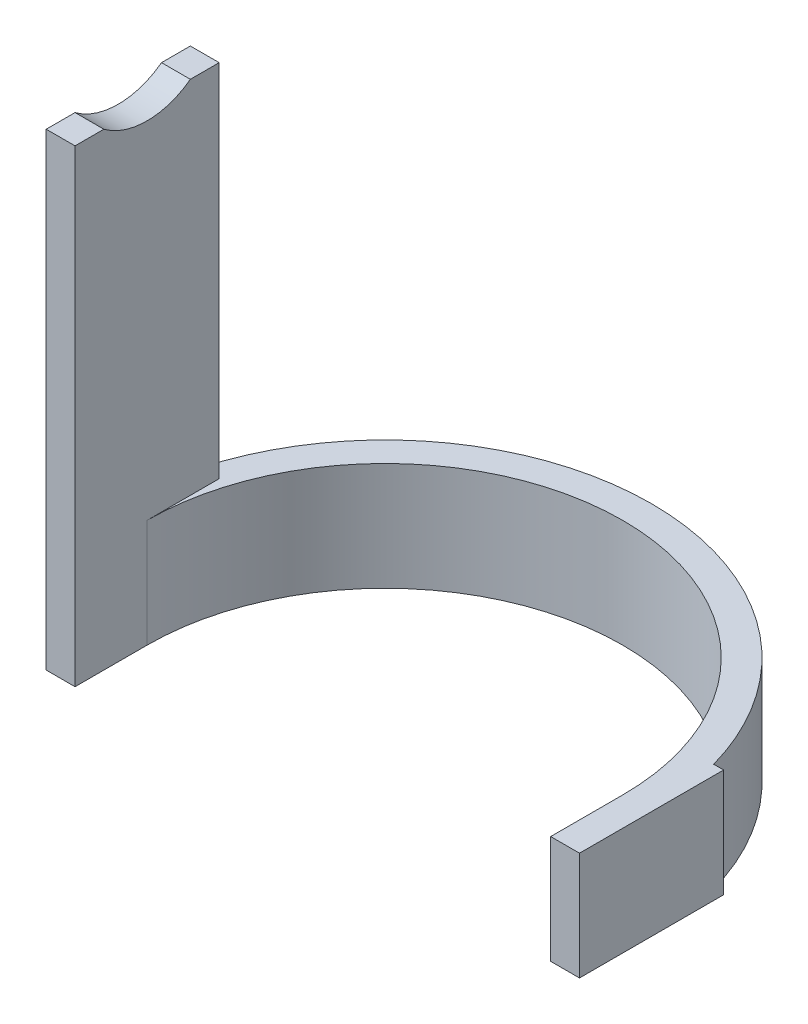
SolidWorks part; units mm, degrees
ref_plane "Front" through (0, 0, 0) normal (0, 0, 1) x (1, 0, 0)
ref_plane "Top" through (0, 0, 0) normal (0, 1, 0) x (1, 0, 0)
ref_plane "Right" through (0, 0, 0) normal (1, 0, 0) x (0, 0, -1)
sketch "草图1" plane through (0, 0, 0) normal (0, 1, 0) x (1, 0, 0)
  line L0 (-72.3418, 0) -> (74, 0) construction
  line L1 (0, 74) -> (0, -74) construction
  line L3 (-74, 20) -> (-71.2461, 20)
  line L4 (-74, 20) -> (-74, -20)
  line L5 (-74, -20) -> (-66, -20)
  line L6 (-66, 0) -> (-66, -20)
  line L7 (74, 20) -> (71.2461, 20)
  line L8 (74, 20) -> (74, -20)
  line L9 (74, -20) -> (66, -20)
  line L10 (66, 0) -> (66, -20)
  arc A0 (71.2461, 20) -> (-71.2461, 20) centre (0, 0) ccw
  arc A1 (66, 0) -> (-66, 0) centre (0, 0) ccw
  dimension "D1" = 40
  dimension "D2" = 20
  dimension "D3" = 8
  dimension "D4" = 8
  dimension "D6" = 40
  dimension "D7" = 20
extrude "凸台-拉伸1" add sketch "草图1" along normal blind 30
sketch "草图2" plane through (0, 30, 0) normal (0, 1, 0) x (1, 0, 0)
  line L1 (-74, -20) -> (-66, -20)
  line L2 (-74, -20) -> (-74, 20)
  line L3 (-74, 20) -> (-66, 20)
  line L4 (-66, -20) -> (-66, 20)
  line L5 (66, -20) -> (74, -20)
  line L6 (66, -20) -> (66, 20)
  line L7 (66, 20) -> (74, 20)
  line L8 (74, -20) -> (74, 20)
  dimension "D1" = 8
extrude "凸台-拉伸2" add sketch "草图2" along normal blind 100
sketch "草图3" plane through (-74, 0, 0) normal (-1, 0, 0) x (0, 0, 1)
  line L0 (-20, 130) -> (20, 130) construction
  circle A0 centre (0, 146) radius 20
  dimension "D1" = 16
extrude "切除-拉伸1" cut sketch "草图3" against normal through all
sketch "草图4" plane through (-74, 0, 0) normal (-1, 0, 0) x (0, 0, 1)
  line L1 (-20, 30) -> (29.7839, 30)
  line L2 (-20, 30) -> (-20, 136.1459)
  line L3 (-20, 136.1459) -> (29.7839, 136.1459)
  line L4 (29.7839, 30) -> (29.7839, 136.1459)
sketch "草图5" plane through (74, 0, 0) normal (1, 0, 0) x (0, 0, -1)
  line L1 (20, 30) -> (-67.0077, 30)
  line L2 (20, 30) -> (20, 135.1923)
  line L3 (20, 135.1923) -> (-67.0077, 135.1923)
  line L4 (-67.0077, 30) -> (-67.0077, 135.1923)
extrude "切除-拉伸2" cut sketch "草图5" against normal blind 10
